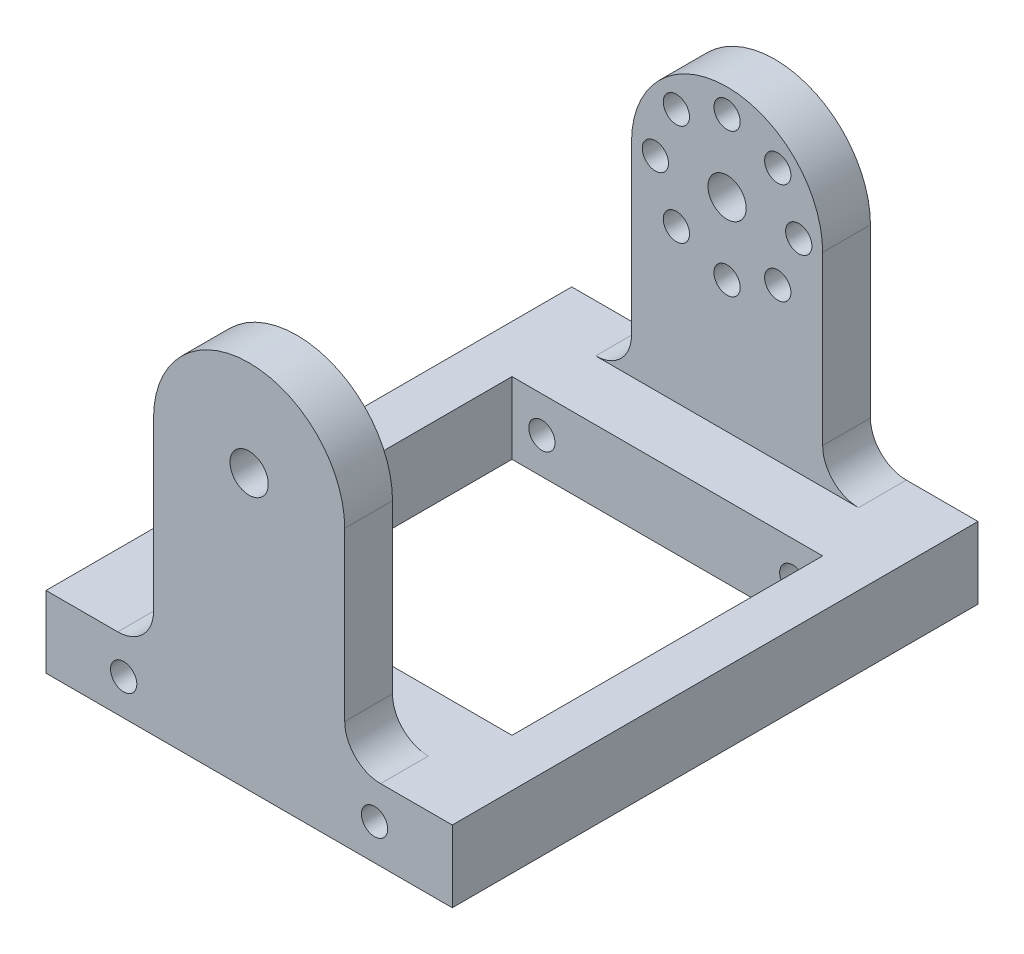
SolidWorks part; units mm, degrees
material "ABS"
ref_plane "正面" through (0, 0, 0) normal (0, 0, 1) x (1, 0, 0)
ref_plane "平面" through (0, 0, 0) normal (0, 1, 0) x (1, 0, 0)
ref_plane "右側面" through (0, 0, 0) normal (1, 0, 0) x (0, 0, -1)
sketch "ｽｹｯﾁ1" plane through (0, 0, 0) normal (0, 0, 1) x (1, 0, 0)
  line L2 (-17, -17) -> (-17, -23)
  line L3 (-17, -23) -> (17, -23)
  line L4 (17, -23) -> (17, -17)
  line L5 (0, 0) -> (0, -23) construction
  line L6 (-17, -20) -> (17, -20) construction
  line L7 (8, 0) -> (8, -14)
  line L8 (11, -17) -> (17, -17)
  line L9 (-8, 0) -> (-8, -14)
  line L10 (-11, -17) -> (-17, -17)
  arc A0 (8, 0) -> (-8, 0) centre (0, 0) ccw
  circle A1 centre (0, 0) radius 6 construction
  circle A2 centre (0, 6) radius 1.1
  circle A3 centre (4.2426, 4.2426) radius 1.1
  circle A4 centre (6, 0) radius 1.1
  circle A5 centre (4.2426, -4.2426) radius 1.1
  circle A6 centre (0, -6) radius 1.1
  circle A7 centre (-4.2426, -4.2426) radius 1.1
  circle A8 centre (-6, 0) radius 1.1
  circle A9 centre (-4.2426, 4.2426) radius 1.1
  circle A10 centre (0, 0) radius 1.6
  arc A11 (-8, -14) -> (-11, -17) centre (-11, -14) cw
  arc A12 (8, -14) -> (11, -17) centre (11, -14) ccw
  point P22 (0, 0)
  dimension "D1" = 16
  dimension "D2" = 12
  dimension "D3" = 2.2
  dimension "D8" = 3.2
  dimension "D9" = 3
  dimension "D5" = 34
  dimension "D6" = 6
  dimension "D7" = 20
  dimension "D4" = 8
extrude "ﾎﾞｽ - 押し出し1" add sketch "ｽｹｯﾁ1" along normal blind 4
sketch "ｽｹｯﾁ2" plane through (0, 0, 4) normal (0, 0, 1) x (1, 0, 0)
  line L0 (17, -17) -> (11, -17) construction
  line L1 (-17, -23) -> (-13, -23)
  line L2 (-17, -23) -> (-17, -17)
  line L3 (-17, -17) -> (-13, -17)
  line L4 (-13, -23) -> (-13, -17)
  line L5 (17, -23) -> (13, -23)
  line L6 (17, -23) -> (17, -17)
  line L7 (17, -17) -> (13, -17)
  line L8 (13, -23) -> (13, -17)
  line L9 (-11, -17) -> (-17, -17) construction
  dimension "D1" = 4
  dimension "D2" = 4
extrude "ﾎﾞｽ - 押し出し2" add sketch "ｽｹｯﾁ2" along normal blind 36
sketch "ｽｹｯﾁ3" plane through (0, 0, 40) normal (0, 0, 1) x (1, 0, 0)
  line L5 (-17, -23) -> (17, -23)
  line L6 (-17, -17) -> (-17, -23)
  line L7 (-11, -17) -> (-17, -17)
  line L8 (-11, -17) -> (-17, -17)
  line L9 (17, -23) -> (17, -17)
  line L10 (-17, -23) -> (17, -23)
  line L11 (-17, -17) -> (-17, -23)
  line L14 (17, -23) -> (17, -17)
  line L17 (-8, 0) -> (-8, -14)
  line L18 (-8, 0) -> (-8, -14)
  line L19 (8, -14) -> (8, 0)
  line L20 (8, -14) -> (8, 0)
  line L21 (17, -17) -> (11, -17)
  line L22 (17, -17) -> (11, -17)
  circle A0 centre (0, 0) radius 1.6
  arc A1 (8, 0) -> (-8, 0) centre (0, 0) ccw
  arc A2 (8, 0) -> (-8, 0) centre (0, 0) ccw
  arc A6 (-11, -17) -> (-8, -14) centre (-11, -14) ccw
  arc A7 (-11, -17) -> (-8, -14) centre (-11, -14) ccw
  arc A8 (8, -14) -> (11, -17) centre (11, -14) ccw
  arc A9 (8, -14) -> (11, -17) centre (11, -14) ccw
  dimension "D2" = 3.2
  dimension "D1" = 0
extrude "ﾎﾞｽ - 押し出し3" add sketch "ｽｹｯﾁ3" along normal blind 4
sketch "ｽｹｯﾁ4" plane through (0, -17, 0) normal (0, 1, 0) x (1, 0, 0)
  line L0 (-13, -40) -> (-13, -4) construction
  line L1 (13, -4) -> (-13, -4)
  line L2 (13, -4) -> (13, -9)
  line L3 (13, -9) -> (-13, -9)
  line L4 (-13, -4) -> (-13, -9)
  line L6 (13, -40) -> (-13, -40)
  line L7 (13, -40) -> (13, -35)
  line L8 (13, -35) -> (-13, -35)
  line L9 (-13, -40) -> (-13, -35)
  dimension "D1" = 5
  dimension "D2" = 5
extrude "ﾎﾞｽ - 押し出し4" add sketch "ｽｹｯﾁ4" against normal up to surface (6 mm away) up to face at (0, -23, 22)
sketch "ｽｹｯﾁ7" plane through (-25.9, 0, 44) normal (0, 0, -1) x (-1, 0, 0)
  line L0 (-42.9, -20) -> (0, -20) construction
  line L1 (-42.9, -23) -> (-42.9, -17) construction
  line L2 (-25.9, -23) -> (-25.9, -17) construction
  line L6 (-38.9, -17) -> (-12.9, -17) construction
  line L7 (-8.9, -23) -> (-42.9, -23) construction
  circle A0 centre (-36.4, -20) radius 1.1
  circle A1 centre (-15.4, -20) radius 1.1
  dimension "D2" = 2.2
  dimension "D1" = 10.5
extrude "ｶｯﾄ - 押し出し2" cut sketch "ｽｹｯﾁ7" along normal through all
